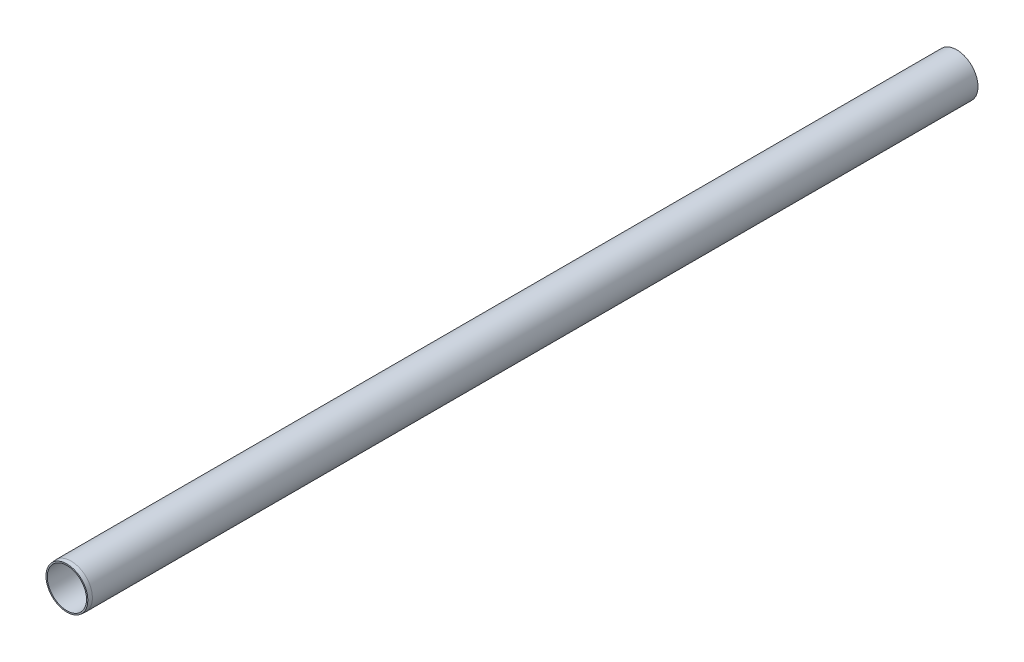
SolidWorks part; units mm, degrees
material "E-Glass Fiber"
ref_plane "Front Plane" through (0, 0, 0) normal (0, 0, 1) x (1, 0, 0)
ref_plane "Top Plane" through (0, 0, 0) normal (0, 1, 0) x (1, 0, 0)
ref_plane "Right Plane" through (0, 0, 0) normal (1, 0, 0) x (0, 0, -1)
sketch "Sketch1" plane through (0, 0, 0) normal (0, 0, 1) x (1, 0, 0)
  circle A0 centre (0, 0) radius 20.6756
  circle A1 centre (0, 0) radius 19.05
  dimension "D1" = 38.1
  dimension "D2" = 41.3512
extrude "Boss-Extrude1" add sketch "Sketch1" along normal blind 863.6
chamfer "Chamfer1" distance 0.3556 angle 85 1 edges at (20.6756, 0, 863.6)
